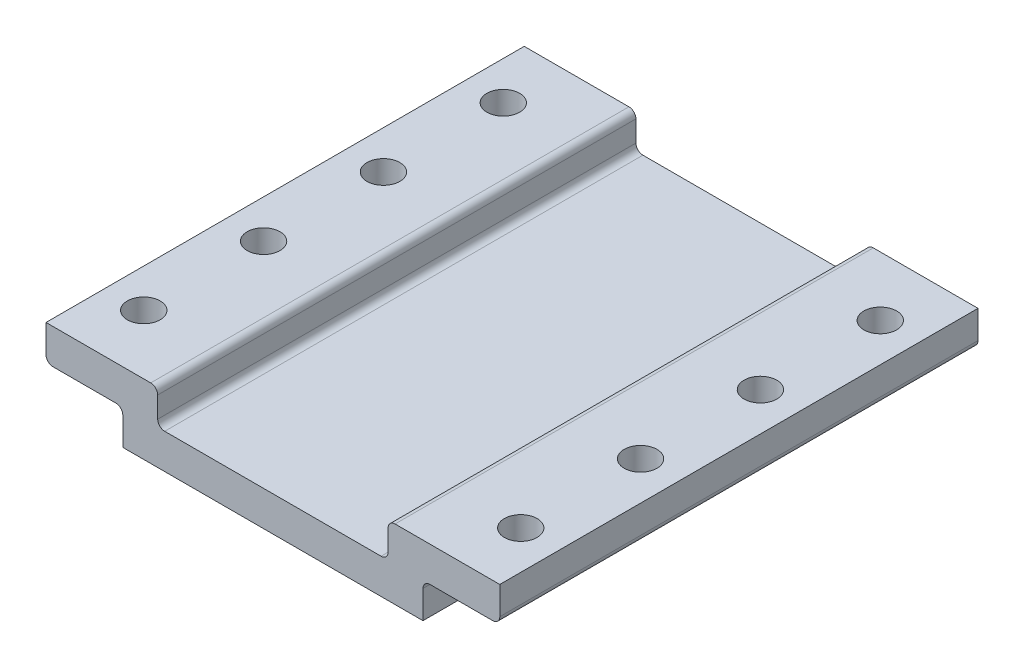
SolidWorks part; units mm, degrees
ref_plane "Front Plane" through (0, 0, 0) normal (0, 0, 1) x (1, 0, 0)
ref_plane "Top Plane" through (0, 0, 0) normal (0, 1, 0) x (1, 0, 0)
ref_plane "Right Plane" through (0, 0, 0) normal (1, 0, 0) x (0, 0, -1)
sketch "Sketch1" plane through (0, 0, 0) normal (0, 1, 0) x (1, 0, 0)
  line L1 (-12.6061, 16.7355) -> (30.3939, 16.7355)
  line L2 (-12.6061, 16.7355) -> (-12.6061, -51.7645)
  line L3 (-12.6061, -51.7645) -> (30.3939, -51.7645)
  line L4 (30.3939, 16.7355) -> (30.3939, -51.7645)
  dimension "D1" = 43
  dimension "D2" = 68.5
extrude "Boss-Extrude1" add sketch "Sketch1" along normal blind 5
sketch "Sketch2" plane through (0, 5, 0) normal (0, 1, 0) x (1, 0, 0)
  line L0 (30.3939, 16.7355) -> (-12.6061, 16.7355) construction
  line L1 (-7.6061, 16.7355) -> (-23.6061, 16.7355)
  line L2 (-7.6061, 16.7355) -> (-7.6061, -51.7645)
  line L3 (-7.6061, -51.7645) -> (-23.6061, -51.7645)
  line L4 (-23.6061, 16.7355) -> (-23.6061, -51.7645)
  line L5 (-12.6061, 16.7355) -> (-12.6061, -51.7645) construction
  line L10 (-12.6061, -51.7645) -> (30.3939, -51.7645) construction
  dimension "D1" = 5
  dimension "D2" = 16
extrude "Boss-Extrude2" add sketch "Sketch2" along normal blind 5
sketch "Sketch3" plane through (0, 10, 0) normal (0, 1, 0) x (1, 0, 0)
  line L0 (-18.1061, 16.7355) -> (-18.1061, -53.4886) construction
  line L1 (-7.6061, 16.7355) -> (-23.6061, 16.7355) construction
  line L2 (-23.6061, 16.7355) -> (-23.6061, -51.7645) construction
  line L3 (-23.6061, -51.7645) -> (-7.6061, -51.7645) construction
  circle A0 centre (-18.1061, 8.2355) radius 2.35
  circle A1 centre (-18.1061, -8.9312) radius 2.35
  circle A2 centre (-18.1061, -26.0978) radius 2.35
  circle A3 centre (-18.1061, -43.2645) radius 2.35
  dimension "D2" = 4.7
  dimension "D5" = 8.5
  dimension "D1" = 5.5
  dimension "D3" = 8.5
  dimension "D4" = 4
ref_plane "Plane1" through (8.8939, 0, 0) normal (1, 0, 0) x (0, 0, -1)
extrude "Cut-Extrude1" cut sketch "Sketch3" against normal up to next
mirror "Mirror1" about plane through (8.8939, 0, 0) normal (1, 0, 0) of "Boss-Extrude2", "Cut-Extrude1"
fillet "Fillet1" radius 1 8 edges at (41.3939, 5, 17.5145) (30.3939, 5, 17.5145) (-23.6061, 5, 17.5145) (-12.6061, 5, 17.5145) (25.3939, 5, 17.5145) (-7.6061, 5, 17.5145) (25.3939, 10, 17.5145) (-7.6061, 10, 17.5145)
chamfer "Chamfer1" distance 1 angle 45 8 edges at (35.8939, 5, -10.5855) (35.8939, 5, 6.5812) (35.8939, 5, 23.7478) (35.8939, 5, 40.9145) (-18.1061, 5, -10.5855) (-18.1061, 5, 6.5812) (-18.1061, 5, 23.7478) (-18.1061, 5, 40.9145)
